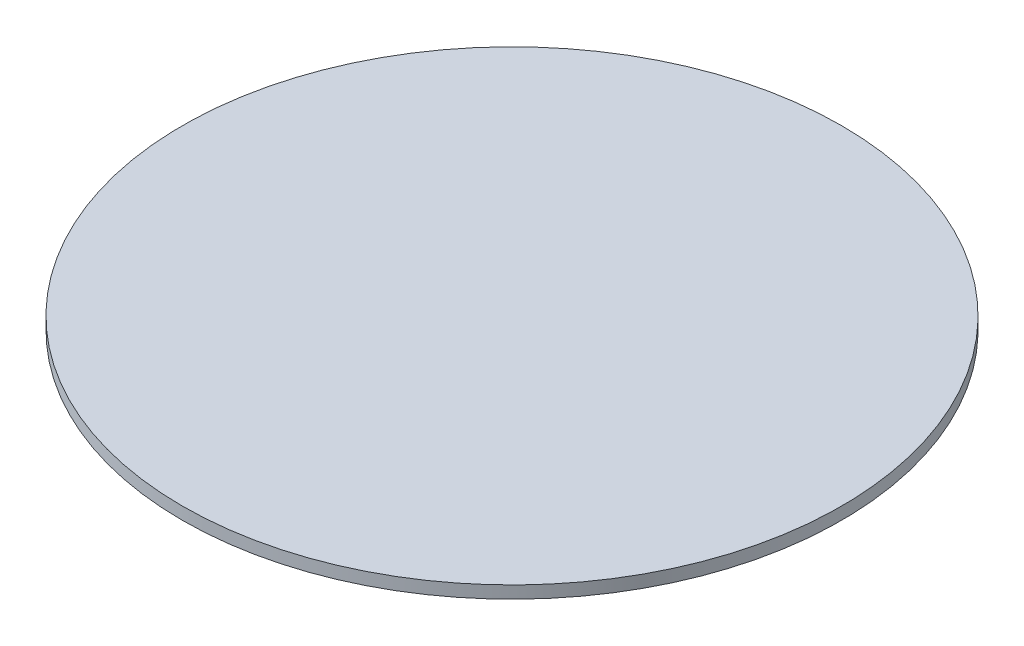
SolidWorks part; units mm, degrees
ref_plane "Front Plane" through (0, 0, 0) normal (0, 0, 1) x (1, 0, 0)
ref_plane "Top Plane" through (0, 0, 0) normal (0, 1, 0) x (1, 0, 0)
ref_plane "Right Plane" through (0, 0, 0) normal (1, 0, 0) x (0, 0, -1)
other "Configuration Table"
sketch "Sketch1" plane through (0, 0, 0) normal (0, 1, 0) x (1, 0, 0)
  circle A0 centre (0, 0) radius 160
extrude "TEPSI_disk_D320_alu_1.5" add sketch "Sketch1" along normal blind 6 separate body
